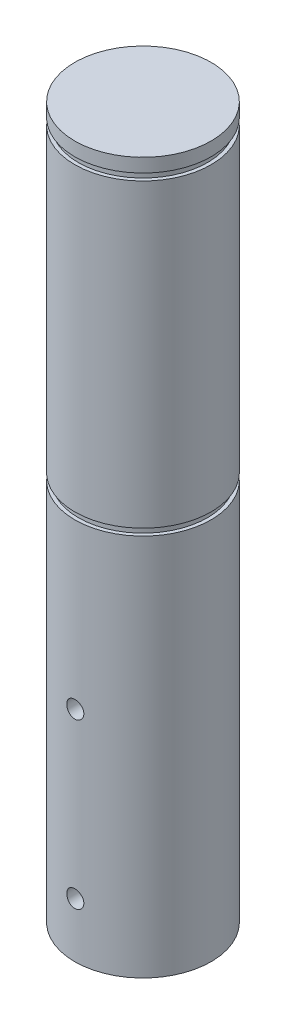
SolidWorks part; units mm, degrees
material "延性铁"
ref_plane "前视基准面" through (0, 0, 0) normal (0, 0, 1) x (1, 0, 0)
ref_plane "上视基准面" through (0, 0, 0) normal (0, 1, 0) x (1, 0, 0)
ref_plane "右视基准面" through (0, 0, 0) normal (1, 0, 0) x (0, 0, -1)
sketch "草图1" plane through (0, 0, 0) normal (0, 1, 0) x (1, 0, 0)
  circle A0 centre (5.9, 0) radius 9.975
  dimension "D1" = 19.95
extrude "凸台-拉伸1" add sketch "草图1" along normal blind 40
ref_plane "基准面1" through (0, 20, 0) normal (0, -1, 0) x (-1, 0, 0)
ref_plane "基准面2" through (0, 0, 9.975) normal (0, 0, 1) x (1, 0, 0)
sketch "草图5" plane through (0, 40, 0) normal (0, 1, 0) x (1, 0, 0)
  circle A0 centre (5.9, 0) radius 9.975
  dimension "D1" = 19.95
extrude "16mm 铰链间距" add sketch "草图5" along normal blind 16
sketch "草图6" plane through (0, 56, 0) normal (0, 1, 0) x (1, 0, 0)
  circle A0 centre (5.9, 0) radius 9.45
  circle A1 centre (5.9, 0) radius 9.975 construction
  dimension "D1" = 18.9
extrude "卡簧1" add sketch "草图6" along normal blind 1
sketch "草图7" plane through (0, 57, 0) normal (0, 1, 0) x (1, 0, 0)
  circle A0 centre (5.9, 0) radius 9.975
  dimension "D1" = 19.95
extrude "凸台-拉伸4" add sketch "草图7" along normal blind 44
sketch "草图8" plane through (0, 101, 0) normal (0, 1, 0) x (1, 0, 0)
  circle A0 centre (5.9, 0) radius 9.45
  dimension "D1" = 18.9
extrude "卡簧2" add sketch "草图8" along normal blind 1
sketch "草图9" plane through (0, 102, 0) normal (0, 1, 0) x (1, 0, 0)
  circle A0 centre (5.9, 0) radius 9.975
  circle A1 centre (5.9, 0) radius 9.45 construction
  dimension "D1" = 19.95
extrude "凸台-拉伸6" add sketch "草图9" along normal blind 2
hole_wizard "M3 螺纹孔7" positions "草图21" profile "草图22" tap size "M3" standard "GB"
sketch "草图21" plane through (0, 0, 9.975) normal (0, 0, 1) x (1, 0, 0)
  line L0 (-4.075, 0) -> (15.875, 0) construction
  line L1 (5.9, 8) -> (5.9, 0) construction
  point P0 (5.9, 8)
  dimension "D1" = 8
sketch "草图22" plane through (5.9, 8, 9.975) normal (1, 0, 0) x (0, -1, 0)
  line L0 (0, 0) -> (0, 8.2511)
  line L1 (0, 8.2511) -> (1.25, 7.5)
  line L2 (1.25, 7.5) -> (1.25, 0)
  line L5 (1.25, 0) -> (0, 0)
  line L10 (0, 8.2511) -> (-1.25, 7.5) construction
  line L11 (0, -6.35) -> (0, 107.95) construction
  dimension "螺纹孔钻头直径" = 2.5
  dimension "螺纹孔钻头深度" = 7.5
  dimension "导头角度" = 118
cosmetic thread "孔螺蚊线9" parameters "D1"=6, "D2"=3
mirror "镜向1" about plane through (0, 20, 0) normal (0, -1, 0) of "M3 螺纹孔7"
